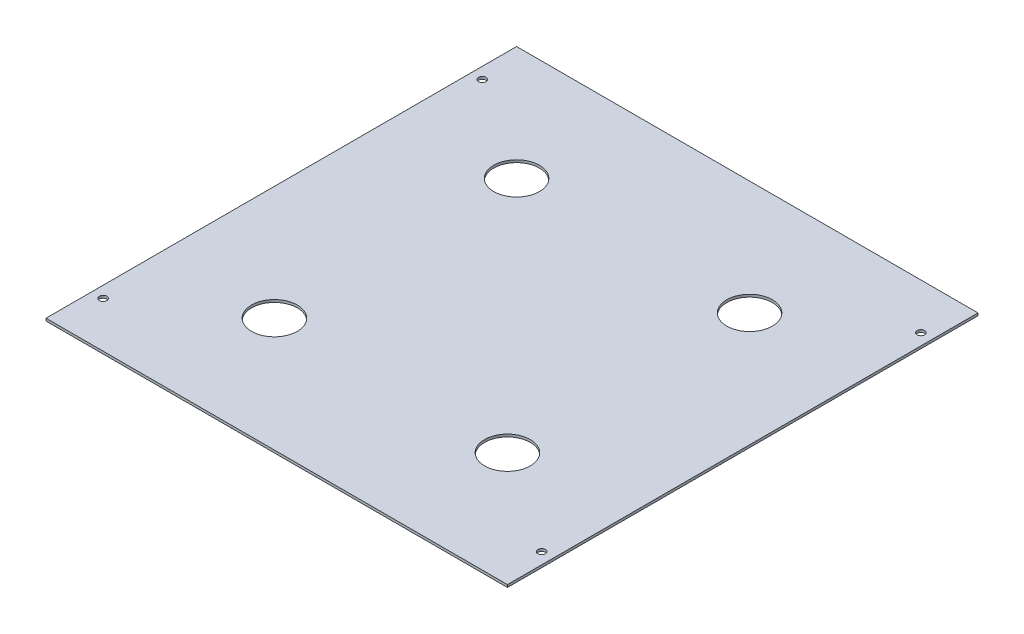
SolidWorks part; units mm, degrees
material "6063-T1"
ref_plane "Front Plane" through (0, 0, 0) normal (0, 0, 1) x (1, 0, 0)
ref_plane "Top Plane" through (0, 0, 0) normal (0, 1, 0) x (1, 0, 0)
ref_plane "Right Plane" through (0, 0, 0) normal (1, 0, 0) x (0, 0, -1)
sketch "Sketch1" plane through (0, 0, 0) normal (0, 1, 0) x (1, 0, 0)
  line L1 (0, 0) -> (202, 0)
  line L2 (0, 0) -> (0, 206)
  line L3 (0, 206) -> (202, 206)
  line L4 (202, 0) -> (202, 206)
  circle A8 centre (5, 186) radius 1.65
  circle A9 centre (50, 156) radius 10
  circle A10 centre (152, 156) radius 10
  circle A11 centre (50, 50) radius 10
  circle A12 centre (152, 50) radius 10
  circle A13 centre (5, 20) radius 1.65
  circle A14 centre (197, 20) radius 1.65
  circle A15 centre (197, 186) radius 1.65
  dimension "D4" = 20
  dimension "D5" = 20
  dimension "D6" = 5
  dimension "D7" = 20
  dimension "D8" = 5
  dimension "D9" = 5
  dimension "D10" = 20
  dimension "D11" = 3.3
  dimension "D12" = 20
  dimension "D13" = 50
  dimension "D14" = 50
  dimension "D15" = 50
  dimension "D16" = 50
  dimension "D17" = 50
  dimension "D18" = 50
  dimension "D19" = 50
  dimension "D20" = 50
  dimension "D1" = 206
  dimension "D2" = 202
  dimension "D3" = 5
extrude "Boss-Extrude1" add sketch "Sketch1" along normal blind 1.1
